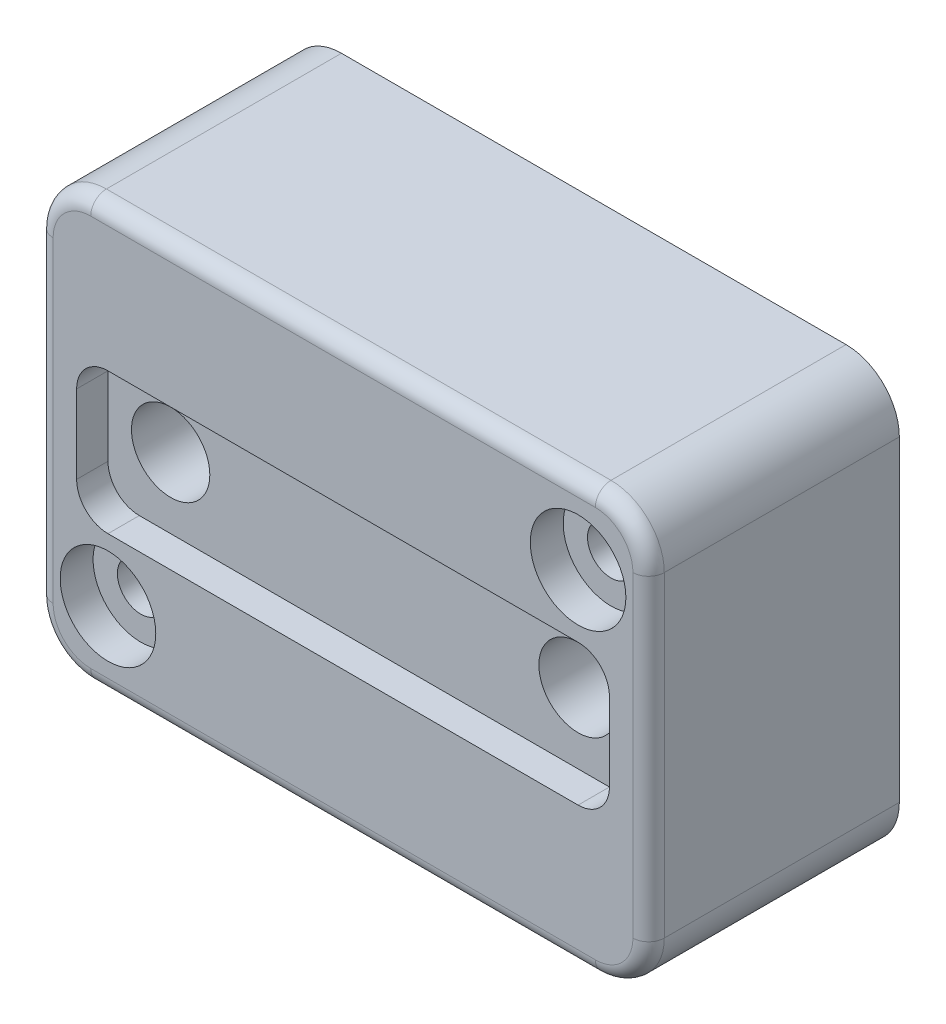
SolidWorks part; units mm, degrees
ref_plane "Ebene vorne" through (0, 0, 0) normal (0, 0, 1) x (1, 0, 0)
ref_plane "Ebene oben" through (0, 0, 0) normal (0, 1, 0) x (1, 0, 0)
ref_plane "Ebene rechts" through (0, 0, 0) normal (1, 0, 0) x (0, 0, -1)
sketch "Skizze1" plane through (0, 0, 0) normal (0, 0, 1) x (1, 0, 0)
  line L0 (0, 0) -> (0, 1.2431) construction
  line L1 (-16.1, 13.5) -> (16.1, 13.5)
  line L2 (-19.5, 10.1) -> (-19.5, -10.1)
  line L3 (-16.1, -13.5) -> (16.1, -13.5)
  line L4 (19.5, 10.1) -> (19.5, -10.1)
  line L5 (0, 0) -> (2.7606, 0) construction
  line L6 (0, 0) -> (-18.5042, 12.5042) construction
  arc A0 (16.1, 13.5) -> (19.5, 10.1) centre (16.1, 10.1) cw
  arc A1 (16.1, -13.5) -> (19.5, -10.1) centre (16.1, -10.1) ccw
  arc A2 (-19.5, -10.1) -> (-16.1, -13.5) centre (-16.1, -10.1) ccw
  arc A3 (-16.1, 13.5) -> (-19.5, 10.1) centre (-16.1, 10.1) ccw
  circle A4 centre (15, 8.5) radius 1.5
  circle A5 centre (-15, -8.5) radius 1.5
  point P18 (0, 0)
  dimension "D3" = 3.4
  dimension "D4" = 3
  dimension "D6" = 3
  dimension "D1" = 13.5
  dimension "D2" = 39
  dimension "D5" = 8.5
  dimension "D7" = 8.5
  dimension "D8" = 15
  dimension "D9" = 15
extrude "Aufsatz-Linear austragen1" add sketch "Skizze1" along normal blind 16
sketch "Skizze2" plane through (0, 0, 16) normal (0, 0, 1) x (1, 0, 0)
  line L0 (0, 0) -> (-26.466, 0) construction
  line L1 (-26.466, 0) -> (23.4019, 0) construction
  line L2 (0, 0) -> (0, 14.7938) construction
  line L4 (-15, 4.5) -> (15, 4.5)
  line L5 (-17, 2.5) -> (-17, -2.5)
  line L6 (-15, -4.5) -> (15, -4.5)
  line L7 (17, 2.5) -> (17, -2.5)
  arc A0 (15, 4.5) -> (17, 2.5) centre (15, 2.5) cw
  arc A1 (15, -4.5) -> (17, -2.5) centre (15, -2.5) ccw
  arc A2 (-17, -2.5) -> (-15, -4.5) centre (-15, -2.5) ccw
  arc A3 (-15, 4.5) -> (-17, 2.5) centre (-15, 2.5) ccw
  point P11 (17, 4.5)
  point P16 (-17, -4.5)
  point P19 (-17, 4.5)
  dimension "D3" = 2
  dimension "D1" = 34
  dimension "D2" = 9
extrude "Schnitt-Linear austragen1" cut sketch "Skizze2" against normal blind 2
sketch "Skizze3" plane through (0, 0, 14) normal (0, 0, 1) x (1, 0, 0)
  line L0 (0, 0) -> (0, 14.7363) construction
  line L1 (0, 0) -> (-23.0189, 0) construction
  line L2 (-23.0189, 0) -> (22.4444, 0) construction
  circle A0 centre (-13, 0) radius 2.5
  circle A1 centre (13, 0) radius 2.5
  dimension "D1" = 5
  dimension "D2" = 26
extrude "Schnitt-Linear austragen2" cut sketch "Skizze3" against normal through all
sketch "Skizze4" plane through (0, 0, 16) normal (0, 0, 1) x (1, 0, 0)
  line L0 (13.5, 8.5) -> (16.5, 8.5) construction
  line L1 (15, 10) -> (15, 7) construction
  circle A0 centre (15, 8.5) radius 1.5 construction
  circle A1 centre (15, 8.5) radius 3.05
  circle A2 centre (-15, -8.5) radius 3.05
  point P9 (-15, -8.5)
  dimension "D1" = 6.1
  dimension "D2" = 6.1
extrude "Schnitt-Linear austragen3" cut sketch "Skizze4" against normal blind 2.1
fillet "Verrundung1" radius 1 8 edges at (-18.5042, 12.5042, 16) (-18.5042, -12.5042, 16) (0, -13.5, 16) (18.5042, -12.5042, 16) (18.5042, 12.5042, 16) (19.5, 0, 16) (0, 13.5, 16) (-19.5, 0, 16)
